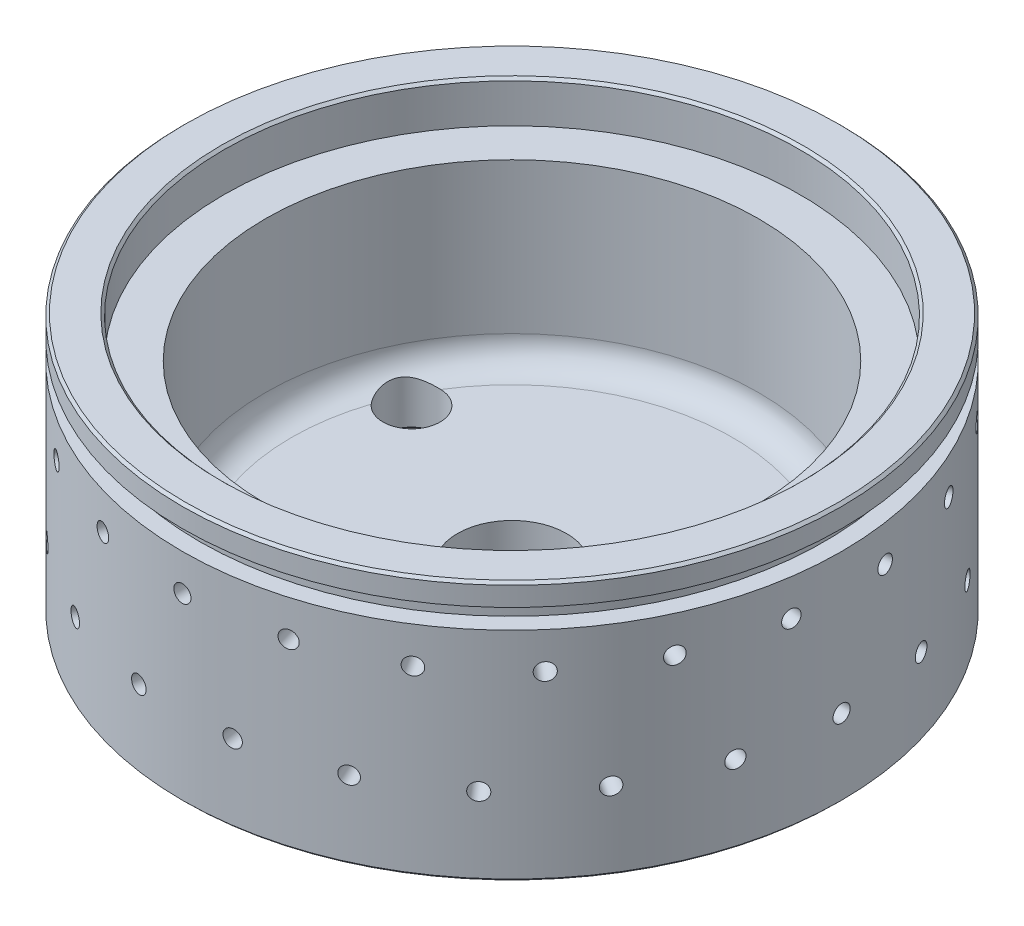
SolidWorks part; units mm, degrees
material "3.1325 (EN-AW 2017A)"
ref_plane "Front Plane" through (0, 0, 0) normal (0, 0, 1) x (1, 0, 0)
ref_plane "Top Plane" through (0, 0, 0) normal (0, 1, 0) x (1, 0, 0)
ref_plane "Right Plane" through (0, 0, 0) normal (1, 0, 0) x (0, 0, -1)
sketch "Sketch1" plane through (0, 0, 0) normal (0, 0, 1) x (1, 0, 0)
  line L0 (0, -55.1447) -> (0, 55.1447) construction
  line L1 (0, 0) -> (63.5, 0)
  line L2 (63.5, 0) -> (63.5, 50)
  line L3 (63.5, 50) -> (55.5, 50)
  line L4 (55.5, 50) -> (55.5, 42)
  line L5 (55.5, 42) -> (47.5, 42)
  line L6 (47.5, 42) -> (47.5, 8)
  line L7 (47.5, 8) -> (0, 8)
  line L8 (0, 8) -> (0, 0)
  point P4 (0, 0)
  dimension "D1" = 127
  dimension "D2" = 50
  dimension "D3" = 95
  dimension "D4" = 111
  dimension "D5" = 8
  dimension "D6" = 34
revolve "Revolve1" add sketch "Sketch1" angle 360 about L0
sketch "Sketch2" plane through (0, 0, 0) normal (0, 0, 1) x (1, 0, 0)
  line L0 (0, -69.8687) -> (0, 69.8687) construction
  line L2 (-63.5, 45.8) -> (-60.2, 45.8)
  line L3 (-63.5, 50) -> (-63.5, 0) construction
  line L4 (-60.2, 45.8) -> (-60.2, 42)
  line L5 (-60.2, 42) -> (-63.5, 42)
  line L6 (-63.5, 42) -> (-63.5, 45.8)
  line L7 (63.5, 50) -> (-63.5, 50) construction
  point P4 (0, 0)
  dimension "D1" = 3.3
  dimension "D2" = 4.2
  dimension "D3" = 3.8
revolve "Cut-Revolve1" cut sketch "Sketch2" angle 360 about L0
fillet "Fillet1" radius 5 1 edges at (47.5, 8, 0)
chamfer "Chamfer1" distance 0.5 angle 45 3 edges at (63.5, 0, 0) (63.5, 50, 0) (55.5, 50, 0)
ref_plane "Plane1" through (-63.5, 0, 0) normal (-1, 0, 0) x (0, 0, 1)
hole_wizard "M4x0.7 Tapped Hole1" positions "Sketch3" profile "Sketch4" tap size "M4x0.7" standard "ANSI Metric"
sketch "Sketch3" plane through (-63.5, 0, 0) normal (-1, 0, 0) x (0, 0, 1)
  line L0 (-63, 0) -> (63, 0) construction
  point P0 (0, 15)
  dimension "D1" = 15
sketch "Sketch4" plane through (-63.5, 15, 0) normal (0, 1, 0) x (0, 0, 1)
  line L0 (0, 0) -> (0, 10)
  line L1 (0, 10) -> (1.65, 9.0086)
  line L2 (1.65, 9.0086) -> (1.65, 0)
  line L5 (1.65, 0) -> (0, 0)
  line L10 (0, 10) -> (-1.65, 9.0086) construction
  line L11 (0, -6.35) -> (0, 107.95) construction
  dimension "Tap Drill Dia." = 3.3
  dimension "Tap Drill Depth" = 10
  dimension "Drill Angle" = 118
cosmetic thread "Hole Thread1" parameters "D1"=6, "D2"=4
pattern_circular "CirPattern1" count 22 over 360 about axis through (0, -55.1447, 0) along (0, -1, 0) of "M4x0.7 Tapped Hole1"
cosmetic thread "Hole Thread2" parameters "D1"=6, "D2"=4
cosmetic thread "Hole Thread3" parameters "D1"=6, "D2"=4
cosmetic thread "Hole Thread4" parameters "D1"=6, "D2"=4
cosmetic thread "Hole Thread5" parameters "D1"=6, "D2"=4
cosmetic thread "Hole Thread6" parameters "D1"=6, "D2"=4
cosmetic thread "Hole Thread7" parameters "D1"=6, "D2"=4
cosmetic thread "Hole Thread8" parameters "D1"=6, "D2"=4
cosmetic thread "Hole Thread9" parameters "D1"=6, "D2"=4
cosmetic thread "Hole Thread10" parameters "D1"=6, "D2"=4
cosmetic thread "Hole Thread11" parameters "D1"=6, "D2"=4
cosmetic thread "Hole Thread12" parameters "D1"=6, "D2"=4
cosmetic thread "Hole Thread13" parameters "D1"=6, "D2"=4
cosmetic thread "Hole Thread14" parameters "D1"=6, "D2"=4
cosmetic thread "Hole Thread15" parameters "D1"=6, "D2"=4
cosmetic thread "Hole Thread16" parameters "D1"=6, "D2"=4
cosmetic thread "Hole Thread17" parameters "D1"=6, "D2"=4
cosmetic thread "Hole Thread18" parameters "D1"=6, "D2"=4
cosmetic thread "Hole Thread19" parameters "D1"=6, "D2"=4
cosmetic thread "Hole Thread20" parameters "D1"=6, "D2"=4
cosmetic thread "Hole Thread21" parameters "D1"=6, "D2"=4
cosmetic thread "Hole Thread22" parameters "D1"=6, "D2"=4
ref_plane "Plane2" through (-62.8537, 0, -9.037) normal (-0.9898, 0, -0.1423) x (0, -1, 0)
hole_wizard "M4x0.7 Tapped Hole2" positions "Sketch5" profile "Sketch6" tap size "M4x0.7" standard "ANSI Metric"
sketch "Sketch5" plane through (-62.8537, 0, -9.037) normal (-0.9898, 0, -0.1423) x (0, -1, 0)
  line L0 (0, -63) -> (0, 63) construction
  point P0 (-35, 0)
  dimension "D1" = 35
sketch "Sketch6" plane through (-62.8537, 35, -9.037) normal (0, 1, 0) x (-0.1423, 0, 0.9898)
  line L0 (0, 0) -> (0, 10)
  line L1 (0, 10) -> (1.65, 9.0086)
  line L2 (1.65, 9.0086) -> (1.65, 0)
  line L5 (1.65, 0) -> (0, 0)
  line L10 (0, 10) -> (-1.65, 9.0086) construction
  line L11 (0, -6.35) -> (0, 107.95) construction
  dimension "Tap Drill Dia." = 3.3
  dimension "Tap Drill Depth" = 10
  dimension "Drill Angle" = 118
cosmetic thread "Hole Thread23" parameters "D1"=6, "D2"=4
pattern_circular "CirPattern2" count 22 over 360 about axis through (0, -55.1447, 0) along (0, -1, 0) of "M4x0.7 Tapped Hole2"
cosmetic thread "Hole Thread24" parameters "D1"=6, "D2"=4
cosmetic thread "Hole Thread25" parameters "D1"=6, "D2"=4
cosmetic thread "Hole Thread26" parameters "D1"=6, "D2"=4
cosmetic thread "Hole Thread27" parameters "D1"=6, "D2"=4
cosmetic thread "Hole Thread28" parameters "D1"=6, "D2"=4
cosmetic thread "Hole Thread29" parameters "D1"=6, "D2"=4
cosmetic thread "Hole Thread30" parameters "D1"=6, "D2"=4
cosmetic thread "Hole Thread31" parameters "D1"=6, "D2"=4
cosmetic thread "Hole Thread32" parameters "D1"=6, "D2"=4
cosmetic thread "Hole Thread33" parameters "D1"=6, "D2"=4
cosmetic thread "Hole Thread34" parameters "D1"=6, "D2"=4
cosmetic thread "Hole Thread35" parameters "D1"=6, "D2"=4
cosmetic thread "Hole Thread36" parameters "D1"=6, "D2"=4
cosmetic thread "Hole Thread37" parameters "D1"=6, "D2"=4
cosmetic thread "Hole Thread38" parameters "D1"=6, "D2"=4
cosmetic thread "Hole Thread39" parameters "D1"=6, "D2"=4
cosmetic thread "Hole Thread40" parameters "D1"=6, "D2"=4
cosmetic thread "Hole Thread41" parameters "D1"=6, "D2"=4
cosmetic thread "Hole Thread42" parameters "D1"=6, "D2"=4
cosmetic thread "Hole Thread43" parameters "D1"=6, "D2"=4
cosmetic thread "Hole Thread44" parameters "D1"=6, "D2"=4
hole_wizard "G5/8 Tapped Hole1" positions "Sketch7" profile "Sketch8" tap size "G5/8" standard "GB" end condition up to next
sketch "Sketch7" plane through (0, 0, 0) normal (0, -1, 0) x (-1, 0, 0)
  point P0 (0, 0)
sketch "Sketch8" plane through (0, 0, 0) normal (1, 0, 0) x (0, 0, -1)
  line L0 (0, 0) -> (0, 8)
  line L1 (0, 8) -> (10.5, 8)
  line L2 (10.5, 8) -> (10.5, 0)
  line L5 (10.5, 0) -> (0, 0)
  line L11 (0, -6.35) -> (0, 107.95) construction
  dimension "Thru Tap Drill Dia." = 21
  dimension "Thru Tap Drill Depth" = 8
cosmetic thread "Hole Thread45" parameters "D2"=22.911
hole_wizard "G3/8 Tapped Hole1" positions "Sketch9" profile "Sketch10" tap size "G3/8" standard "GB" end condition through all
sketch "Sketch9" plane through (0, 0, 0) normal (0, -1, 0) x (-1, 0, 0)
  point P0 (-37.5, 0)
  dimension "D1" = 37.5
sketch "Sketch10" plane through (37.5, 0, 0) normal (1, 0, 0) x (0, 0, -1)
  line L0 (0, 0) -> (0, 50)
  line L1 (0, 50) -> (7.625, 50)
  line L2 (7.625, 50) -> (7.625, 0)
  line L5 (7.625, 0) -> (0, 0)
  line L11 (0, -6.35) -> (0, 107.95) construction
  dimension "Thru Tap Drill Dia." = 15.25
  dimension "Thru Tap Drill Depth" = 50
cosmetic thread "Hole Thread46" parameters "D2"=16.662
hole_wizard "M12x1.0 Tapped Hole1" positions "Sketch11" profile "Sketch12" tap size "M12x1.0" standard "DIN"
sketch "Sketch11" plane through (0, 0, 0) normal (0, -1, 0) x (-1, 0, 0)
  line L0 (0, 0) -> (-34.636, 34.636) construction
  line L3 (0, 0) -> (-37.5, 0) construction
  line L6 (0, 0) -> (0, 41.8436) construction
  line L9 (0, 0) -> (36.2523, 16.9047) construction
  point P0 (36.2523, 16.9047)
  dimension "D1" = 45
  dimension "D2" = 110
  dimension "D3" = 40
sketch "Sketch12" plane through (-36.2523, 0, -16.9047) normal (1, 0, 0) x (0, 0, -1)
  line L0 (0, 0) -> (0, 27)
  line L1 (0, 27) -> (5.5, 23.6953)
  line L2 (5.5, 23.6953) -> (5.5, 0.525)
  line L3 (5.5, 0.525) -> (6.025, 0)
  line L5 (6.025, 0) -> (0, 0)
  line L6 (-5.5, 0.525) -> (-6.025, 0) construction
  line L10 (0, 27) -> (-5.5, 23.6953) construction
  line L11 (0, -6.35) -> (0, 107.95) construction
  dimension "Tap Drill Dia." = 11
  dimension "Tap Drill Depth" = 27
  dimension "Near C'Sink Dia." = 12.05
  dimension "Near C'Sink Angle" = 90
  dimension "Drill Angle" = 118
cosmetic thread "Hole Thread47" parameters "D1"=24, "D2"=12
